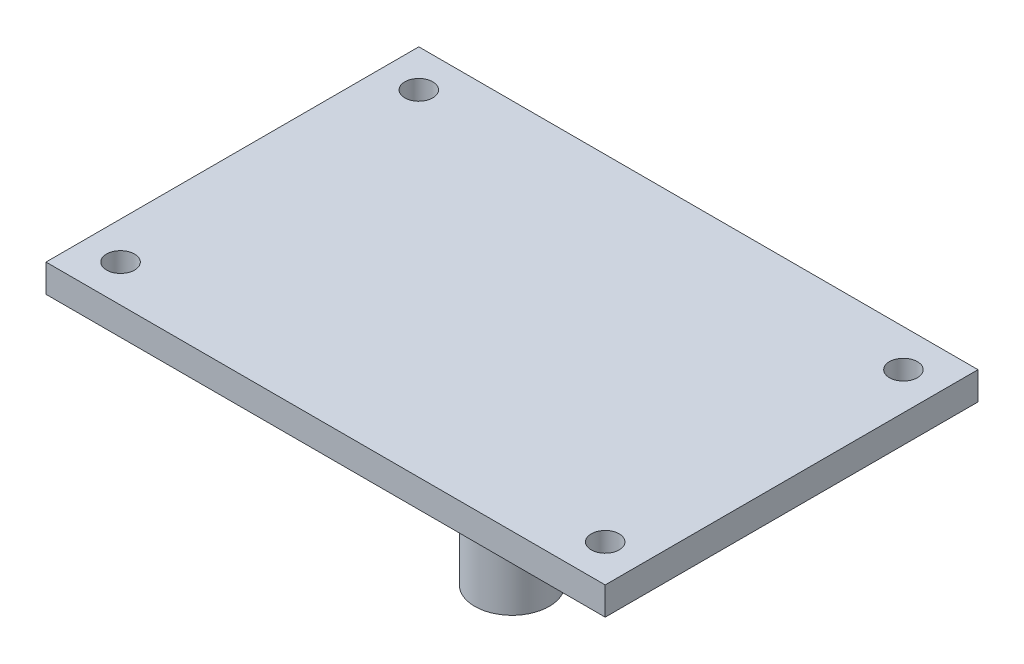
SolidWorks part; units mm, degrees
ref_plane "Front Plane" through (0, 0, 0) normal (0, 0, 1) x (1, 0, 0)
ref_plane "Top Plane" through (0, 0, 0) normal (0, 1, 0) x (1, 0, 0)
ref_plane "Right Plane" through (0, 0, 0) normal (1, 0, 0) x (0, 0, -1)
sketch "Sketch1" plane through (0, 0, 0) normal (0, 1, 0) x (1, 0, 0)
  circle A0 centre (0, 0) radius 4
  dimension "D1" = 8
extrude "Boss-Extrude1" add sketch "Sketch1" along normal blind 18
sketch "Sketch2" plane through (0, 18, 0) normal (0, 1, 0) x (1, 0, 0)
  circle A0 centre (0, 0) radius 5
  dimension "D1" = 10
extrude "Boss-Extrude2" add sketch "Sketch2" along normal blind 4
sketch "Sketch3" plane through (0, 22, 0) normal (0, 1, 0) x (1, 0, 0)
  line L0 (0, -5.5) -> (0, 5.5) construction
  line L1 (-30, 20) -> (30, 20)
  line L2 (-30, 20) -> (-30, -20)
  line L3 (-30, -20) -> (30, -20)
  line L4 (30, 20) -> (30, -20)
  line L5 (-30, 20) -> (30, -20) construction
  line L6 (-30, -20) -> (30, 20) construction
  line L7 (-5.5, 0) -> (5.5, 0) construction
  circle A0 centre (-26, 16) radius 1.5
  circle A1 centre (26, 16) radius 1.5
  circle A2 centre (26, -16) radius 1.5
  circle A3 centre (-26, -16) radius 1.5
  point P0 (0, 0)
  dimension "D3" = 3
  dimension "D1" = 60
  dimension "D2" = 40
  dimension "D4" = 4
  dimension "D5" = 4
extrude "Boss-Extrude3" add sketch "Sketch3" along normal blind 3 contours L1 L4 L3 L2
